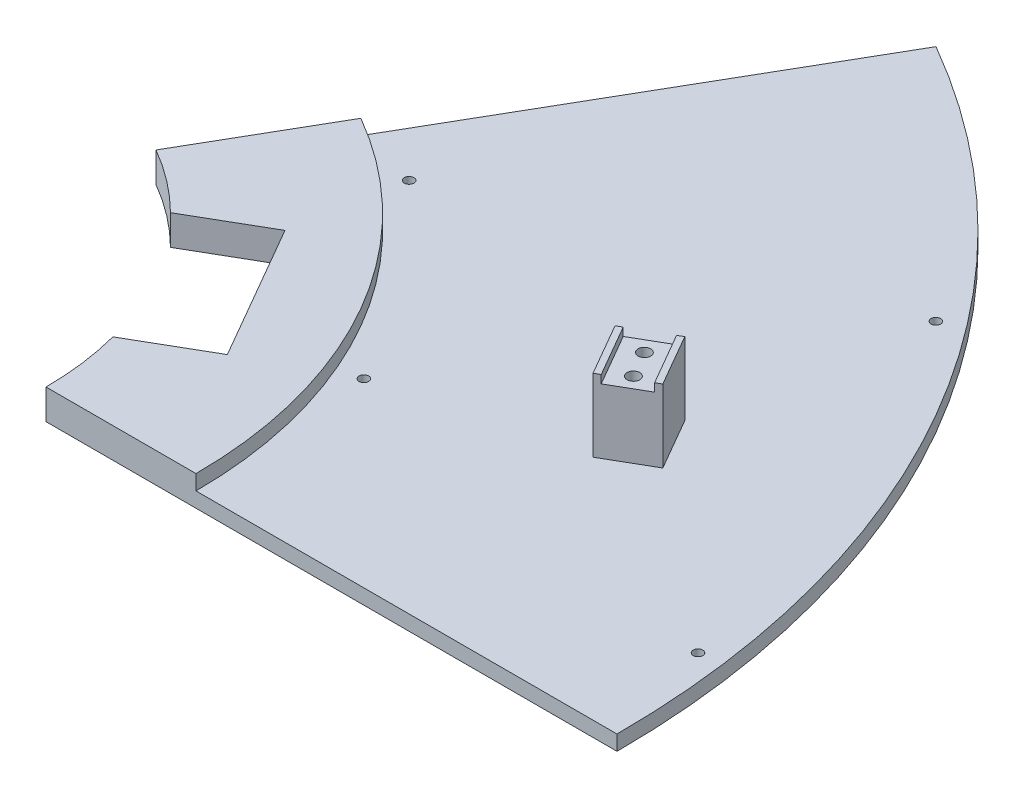
SolidWorks part; units mm, degrees
ref_plane "Ebene vorne" through (0, 0, 0) normal (0, 0, 1) x (1, 0, 0)
ref_plane "Ebene oben" through (0, 0, 0) normal (0, 1, 0) x (1, 0, 0)
ref_plane "Ebene rechts" through (0, 0, 0) normal (1, 0, 0) x (0, 0, -1)
sketch "Skizze1" plane through (0, 0, 0) normal (0, 1, 0) x (1, 0, 0)
  line L0 (0, 0) -> (290, 0)
  line L1 (0, 0) -> (145, 251.1474)
  arc A0 (290, 0) -> (145, 251.1474) centre (0, 0) ccw
  dimension "D1" = 290
  dimension "D2" = 60
extrude "Aufsatz-Linear austragen1" add sketch "Skizze1" along normal blind 5
sketch "Skizze2" plane through (0, 5, 0) normal (0, 1, 0) x (1, 0, 0)
  line L2 (145, 251.1474) -> (0, 0) construction
  line L3 (0, 0) -> (290, 0) construction
  line L4 (0, 0) -> (149.9, 0)
  line L5 (74.95, 129.8172) -> (0, 0)
  arc A0 (74.95, 129.8172) -> (149.9, 0) centre (0, 0) cw
  dimension "D1" = 149.9
extrude "Aufsatz-Linear austragen2" add sketch "Skizze2" along normal blind 5
sketch "Skizze3" plane through (0, 10, 0) normal (0, 1, 0) x (1, 0, 0)
  line L0 (0, 0) -> (129.8172, 74.95) construction
  line L2 (26.2, 45.3797) -> (94.6336, 84.8899)
  line L3 (74.95, 129.8172) -> (0, 0) construction
  line L4 (94.6336, 84.8899) -> (120.8336, 39.5101)
  line L5 (120.8336, 39.5101) -> (52.4, 0)
  line L6 (0, 0) -> (149.9, 0) construction
  line L7 (26.2, 45.3797) -> (0, 0)
  line L8 (0, 0) -> (52.4, 0)
  arc A0 (149.9, 0) -> (74.95, 129.8172) centre (0, 0) ccw construction
  point P10 (107.7336, 62.2)
  dimension "D1" = 52.4
  dimension "D2" = 124.4
extrude "Schnitt-Linear austragen1" cut sketch "Skizze3" against normal through all
sketch "Skizze4" plane through (0, 10, 0) normal (0, 1, 0) x (1, 0, 0)
  line L0 (74.95, 129.8172) -> (26.2, 45.3797) construction
  line L1 (52.4, 0) -> (149.9, 0) construction
  line L2 (100, 0) -> (0, 0)
  line L3 (0, 0) -> (50, 86.6025)
  arc A0 (50, 86.6025) -> (100, 0) centre (0, 0) cw
  dimension "D1" = 100
extrude "Schnitt-Linear austragen2" cut sketch "Skizze4" against normal through all
sketch "Skizze5" plane through (0, 5, 0) normal (0, 1, 0) x (1, 0, 0)
  line L0 (145, 251.1474) -> (74.95, 129.8172) construction
  line L1 (149.9, 0) -> (290, 0) construction
  line L2 (280.0832, 36.8736) -> (0, 0) construction
  line L3 (0, 0) -> (145.511, 60.2726) construction
  line L4 (224.1223, 171.9751) -> (0, 0) construction
  line L5 (0, 0) -> (95.8799, 124.9532) construction
  line L6 (100, 0) -> (149.9, 0) construction
  circle A0 centre (95.8799, 124.9532) radius 1.6
  circle A1 centre (224.1223, 171.9751) radius 1.6
  circle A2 centre (145.511, 60.2726) radius 1.6
  circle A3 centre (280.0832, 36.8736) radius 1.6
  arc A4 (78.75, 136.399) -> (157.5, 0) centre (0, 0) cw construction
  arc A5 (141.25, 244.6522) -> (282.5, 0) centre (0, 0) cw construction
  dimension "D1" = 3.2
  dimension "D2" = 157.5
  dimension "D3" = 282.5
  dimension "D4" = 7.5
  dimension "D5" = 22.5
  dimension "D6" = 30
  dimension "D7" = 30
extrude "Schnitt-Linear austragen3" cut sketch "Skizze5" against normal through all
chamfer "Fase1" distance 2 angle 45 4 edges at (280.0832, 0, -35.2736) (224.1223, 0, -170.3751) (95.8799, 0, -123.3532) (145.511, 0, -58.6726)
sketch "Skizze6" plane through (0, 5, 0) normal (0, 1, 0) x (1, 0, 0)
  line L0 (0, 0) -> (194.8557, 112.5) construction
  line L1 (145, 251.1474) -> (74.95, 129.8172) construction
  line L2 (170.4766, 141.726) -> (181.7349, 148.226) construction
  line L7 (181.7349, 148.226) -> (219.2349, 83.274) construction
  line L8 (219.2349, 83.274) -> (207.9766, 76.774) construction
  line L9 (207.9766, 76.774) -> (170.4766, 141.726) construction
  line L10 (120.8336, 39.5101) -> (94.6336, 84.8899) construction
  line L11 (100, 0) -> (149.9, 0) construction
  line L12 (181.7349, 148.226) -> (207.9766, 76.774) construction
  line L13 (207.9766, 76.774) -> (219.2349, 83.274)
  line L14 (219.2349, 83.274) -> (209.2349, 100.5946)
  line L15 (209.2349, 100.5946) -> (197.9766, 94.0946)
  line L16 (197.9766, 94.0946) -> (207.9766, 76.774)
  arc A1 (225, 0) -> (112.5, 194.8557) centre (0, 0) ccw construction
  point P3 (194.8557, 112.5)
  dimension "D1" = 225
  dimension "D2" = 75
  dimension "D3" = 13
  dimension "D4" = 30
  dimension "D5" = 20
extrude "Aufsatz-Linear austragen3" add sketch "Skizze6" along normal blind 21.5
sketch "Skizze7" plane through (0, 26.5, 0) normal (0, 1, 0) x (1, 0, 0)
  line L0 (206.1057, 93.0144) -> (211.1057, 84.3542) construction
  line L1 (209.2349, 100.5946) -> (207.9766, 76.774) construction
  line L2 (219.2349, 83.274) -> (209.2349, 100.5946) construction
  circle A0 centre (206.1057, 93.0144) radius 2.1
  circle A1 centre (211.1057, 84.3542) radius 2.1
  point P10 (208.6057, 88.6843)
  point P11 (208.6057, 88.6843)
  dimension "D1" = 4.2
  dimension "D2" = 10
extrude "Schnitt-Linear austragen4" cut sketch "Skizze7" against normal through all
sketch "Skizze9" plane through (0, 5, 0) normal (0, 1, 0) x (1, 0, 0)
  line L0 (197.9766, 94.0946) -> (207.9766, 76.774)
  line L1 (207.9766, 76.774) -> (219.2349, 83.274) construction
  line L2 (197.9766, 94.0946) -> (207.9766, 76.774) construction
  line L3 (207.9766, 76.774) -> (206.2445, 75.774)
  line L4 (206.2445, 75.774) -> (196.2445, 93.0946)
  line L5 (196.2445, 93.0946) -> (197.9766, 94.0946)
  line L6 (219.2349, 83.274) -> (220.9669, 84.274)
  line L7 (220.9669, 84.274) -> (210.9669, 101.5946)
  line L8 (210.9669, 101.5946) -> (209.2349, 100.5946)
  line L9 (219.2349, 83.274) -> (209.2349, 100.5946) construction
  line L10 (219.2349, 83.274) -> (209.2349, 100.5946) construction
  line L11 (209.2349, 100.5946) -> (219.2349, 83.274)
  dimension "D1" = 2
extrude "Aufsatz-Linear austragen4" add sketch "Skizze9" along normal blind 24.2
chamfer "Fase2" distance 2.5 angle 45 2 edges at (206.1057, 0, -90.9144) (211.1057, 0, -82.2542)
